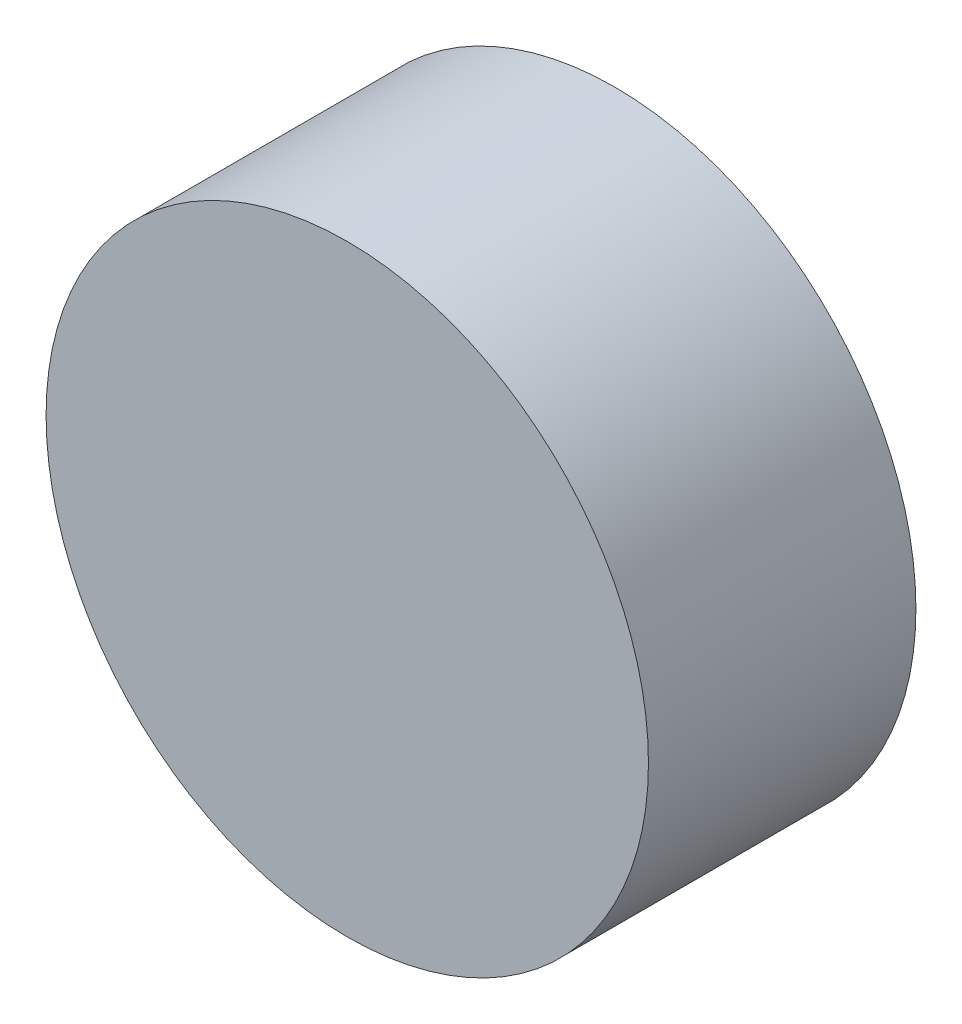
SolidWorks part; units mm, degrees
material "AISI 304"
ref_plane "Front Plane" through (0, 0, 0) normal (0, 0, 1) x (1, 0, 0)
ref_plane "Top Plane" through (0, 0, 0) normal (0, 1, 0) x (1, 0, 0)
ref_plane "Right Plane" through (0, 0, 0) normal (1, 0, 0) x (0, 0, -1)
sketch "Sketch1" plane through (0, 0, 0) normal (0, 0, 1) x (1, 0, 0)
  circle A0 centre (0, 0) radius 1.25
  dimension "D1" = 2.5
extrude "Boss-Extrude1" add sketch "Sketch1" along normal blind 1.11
